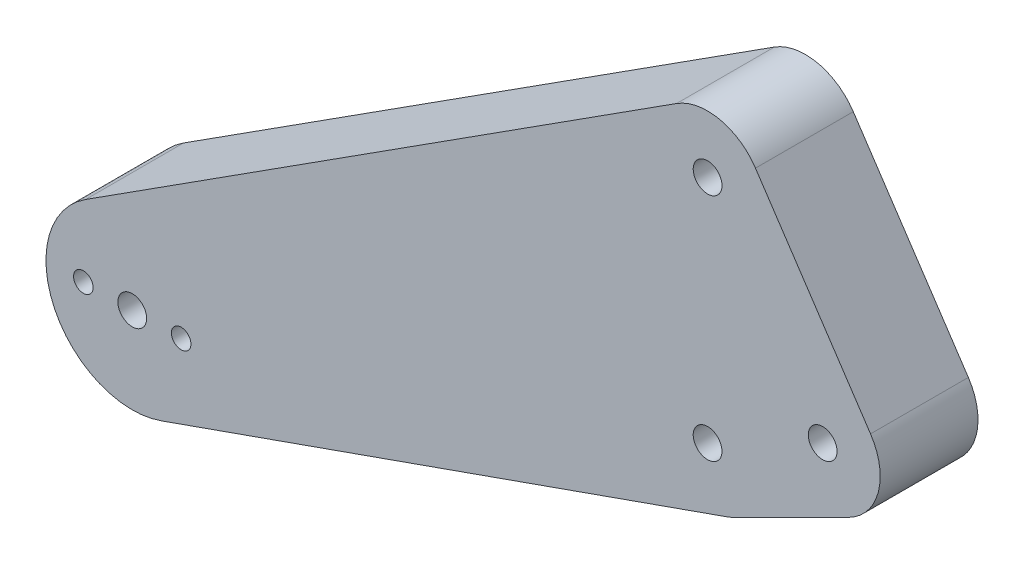
SolidWorks part; units mm, degrees
ref_plane "Front Plane" through (0, 0, 0) normal (0, 0, 1) x (1, 0, 0)
ref_plane "Top Plane" through (0, 0, 0) normal (0, 1, 0) x (1, 0, 0)
ref_plane "Right Plane" through (0, 0, 0) normal (1, 0, 0) x (0, 0, -1)
sketch "Sketch1" plane through (0, 0, 0) normal (0, 0, 1) x (1, 0, 0)
  line L1 (3.3289, -9.4297) -> (-95.0067, -44.1445)
  line L2 (-108.0914, -17.3695) -> (-5.3942, 48.4203)
  line L3 (8.3205, 45.547) -> (28.3205, 15.547)
  line L4 (24.4721, 1.0557) -> (4.4721, -8.9443)
  arc A0 (4.4721, -8.9443) -> (3.3289, -9.4297) centre (0, 0) cw
  arc A1 (-95.0067, -44.1445) -> (-108.0914, -17.3695) centre (-100, -30) cw
  arc A2 (-5.3942, 48.4203) -> (8.3205, 45.547) centre (0, 40) cw
  arc A3 (28.3205, 15.547) -> (24.4721, 1.0557) centre (20, 10) cw
  point P13 (13.8475, -5.7661)
  point P14 (0.0939, 40.3793)
  dimension "D1" = 15
  dimension "D5" = 10
  dimension "D8" = 10
  dimension "D9" = 10
  dimension "D2" = 30
  dimension "D3" = 40
  dimension "D4" = 100
  dimension "D6" = 20
  dimension "D7" = 30
extrude "Boss-Extrude1" add sketch "Sketch1" along normal blind 17
sketch "Sketch2" plane through (0, 0, 17) normal (0, 0, 1) x (1, 0, 0)
  circle A0 centre (-100, -30) radius 2.5
  circle A1 centre (0, 0) radius 2.5
  circle A2 centre (0, 40) radius 2.5
  circle A3 centre (20, 10) radius 2.5
  arc A4 (24.4721, 1.0557) -> (28.3205, 15.547) centre (20, 10) ccw construction
  dimension "D1" = 5
  dimension "D2" = 5
extrude "Cut-Extrude1" cut sketch "Sketch2" against normal through all
sketch "Sketch3" plane through (0, 0, 17) normal (0, 0, 1) x (1, 0, 0)
  line L0 (-108.5, -30) -> (-91.5, -30) construction
  circle A0 centre (-108.5, -30) radius 1.7
  circle A1 centre (-91.5, -30) radius 1.7
  circle A3 centre (-100, -30) radius 2.5 construction
  point P4 (-100, -30)
  dimension "D1" = 3.4
  dimension "D2" = 17
extrude "Cut-Extrude2" cut sketch "Sketch3" against normal through all
sketch "Sketch7" plane through (0, 0, 0) normal (0, 0, -1) x (-1, 0, 0)
  circle A0 centre (100, -30) radius 12.7
  dimension "D1" = 25.4
extrude "Cut-Extrude6" [suppressed] cut sketch "Sketch7" against normal blind 13
sketch "Sketch6" plane through (0, 0, 17) normal (0, 0, 1) x (1, 0, 0)
  circle A0 centre (-100, -30) radius 12.7
  dimension "D1" = 25.4
extrude "Cut-Extrude5" [suppressed] cut sketch "Sketch6" against normal blind 13
sketch "Sketch4" [suppressed] plane through (0, 0, 13) normal (0, 0, -1) x (-1, 0, 0)
  circle A0 centre (100, -30) radius 5.5
  dimension "D1" = 11
extrude "Cut-Extrude3" [suppressed] cut sketch "Sketch4" against normal blind 0.9
sketch "Sketch5" [suppressed] plane through (0, 0, 4) normal (0, 0, 1) x (1, 0, 0)
  circle A0 centre (-100, -30) radius 5.5
  dimension "D1" = 11
extrude "Cut-Extrude4" [suppressed] cut sketch "Sketch5" against normal blind 0.9
